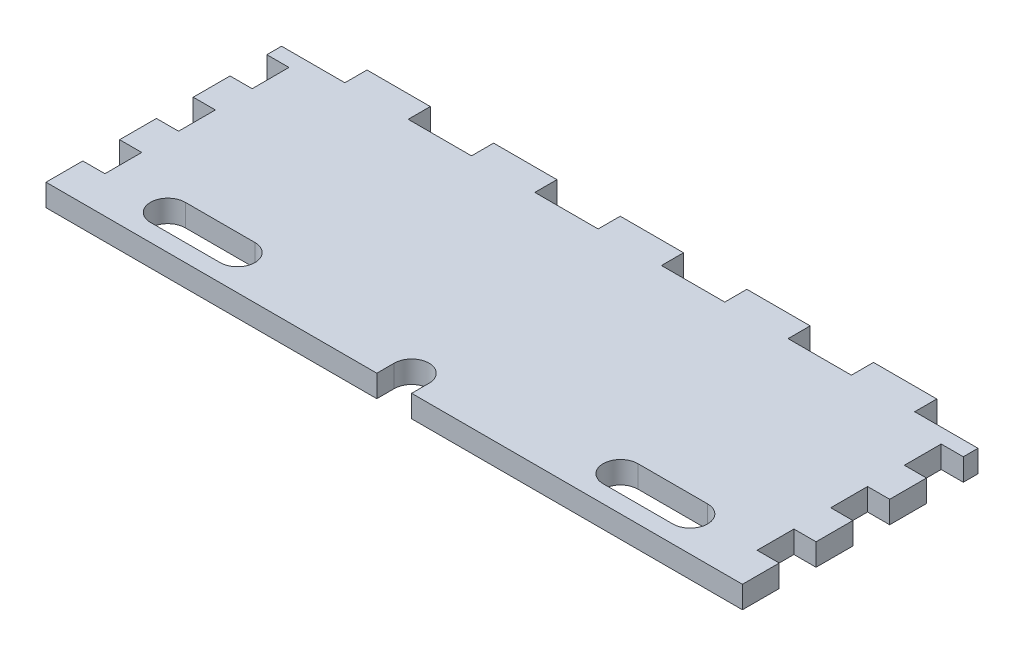
SolidWorks part; units mm, degrees
material "Pin"
ref_plane "Plan de face" through (0, 0, 0) normal (0, 0, 1) x (1, 0, 0)
ref_plane "Plan de dessus" through (0, 0, 0) normal (0, 1, 0) x (1, 0, 0)
ref_plane "Plan de droite" through (0, 0, 0) normal (1, 0, 0) x (0, 0, -1)
sketch "Esquisse1" plane through (0, 0, 0) normal (0, 1, 0) x (1, 0, 0)
  line L1 (-100, 0) -> (100, 0)
  line L2 (-100, 0) -> (-100, 74)
  line L3 (-100, 74) -> (100, 74)
  line L4 (100, 0) -> (100, 74)
  point P4 (0, 0)
  dimension "D1" = 200
  dimension "D2" = 74
extrude "Boss.-Extru.1" add sketch "Esquisse1" along normal blind 6.35
sketch "Esquisse3" plane through (0, 6.35, 0) normal (0, 1, 0) x (1, 0, 0)
  line L0 (-100, 74) -> (-100, 0) construction
  line L1 (-100, 10.5714) -> (-93.65, 10.5714)
  line L2 (-100, 10.5714) -> (-100, 21.1429)
  line L3 (-100, 21.1429) -> (-93.65, 21.1429)
  line L4 (-93.65, 10.5714) -> (-93.65, 21.1429)
  line L5 (-100, 31.7143) -> (-93.65, 31.7143)
  line L6 (-100, 31.7143) -> (-100, 42.2857)
  line L7 (-100, 42.2857) -> (-93.65, 42.2857)
  line L8 (-93.65, 31.7143) -> (-93.65, 42.2857)
  line L10 (-100, 52.8571) -> (-93.65, 52.8571)
  line L11 (-100, 52.8571) -> (-100, 63.4286)
  line L12 (-100, 63.4286) -> (-93.65, 63.4286)
  line L13 (-93.65, 52.8571) -> (-93.65, 63.4286)
  line L18 (-93.65, 63.4286) -> (-93.65, 74) construction
  line L19 (-93.65, 52.8571) -> (-93.65, 42.2857) construction
  line L20 (-93.65, 31.7143) -> (-93.65, 21.1429) construction
  line L21 (100, 74) -> (-100, 74) construction
  line L22 (-93.65, 10.5714) -> (-93.65, 0) construction
  line L23 (-100, 0) -> (100, 0) construction
  dimension "D1" = 6.35
extrude "Enlèv. mat.-Extru.1" cut sketch "Esquisse3" against normal blind 6.35
mirror "Symétrie1" about plane through (0, 0, 0) normal (1, 0, 0) of "Enlèv. mat.-Extru.1"
sketch "Esquisse4" plane through (0, 6.35, 0) normal (0, 1, 0) x (1, 0, 0)
  line L0 (100, 74) -> (-100, 74) construction
  line L1 (-100, 74) -> (-81.8182, 74)
  line L2 (-100, 74) -> (-100, 67.65)
  line L3 (-100, 67.65) -> (-81.8182, 67.65)
  line L4 (-81.8182, 74) -> (-81.8182, 67.65)
  line L5 (-63.6364, 74) -> (-45.4545, 74)
  line L6 (-63.6364, 74) -> (-63.6364, 67.65)
  line L7 (-63.6364, 67.65) -> (-45.4545, 67.65)
  line L8 (-45.4545, 74) -> (-45.4545, 67.65)
  line L9 (-81.8182, 74) -> (-63.6364, 74) construction
  line L10 (-27.2727, 74) -> (-9.0909, 74)
  line L11 (-27.2727, 74) -> (-27.2727, 67.65)
  line L12 (-27.2727, 67.65) -> (-9.0909, 67.65)
  line L13 (-9.0909, 74) -> (-9.0909, 67.65)
  line L14 (9.0909, 74) -> (27.2727, 74)
  line L15 (9.0909, 74) -> (9.0909, 67.65)
  line L16 (9.0909, 67.65) -> (27.2727, 67.65)
  line L17 (27.2727, 74) -> (27.2727, 67.65)
  line L18 (45.4545, 74) -> (63.6364, 74)
  line L19 (45.4545, 74) -> (45.4545, 67.65)
  line L20 (45.4545, 67.65) -> (63.6364, 67.65)
  line L21 (63.6364, 74) -> (63.6364, 67.65)
  line L22 (81.8182, 74) -> (100, 74)
  line L23 (81.8182, 74) -> (81.8182, 67.65)
  line L24 (81.8182, 67.65) -> (100, 67.65)
  line L25 (100, 74) -> (100, 67.65)
  line L26 (-45.4545, 74) -> (-27.2727, 74) construction
  line L27 (-9.0909, 74) -> (9.0909, 74) construction
  line L28 (27.2727, 74) -> (45.4545, 74) construction
  line L29 (63.6364, 74) -> (81.8182, 74) construction
  dimension "D1" = 6.35
extrude "Enlèv. mat.-Extru.2" cut sketch "Esquisse4" against normal blind 6.35
sketch "Esquisse5" plane through (0, 6.35, 0) normal (0, 1, 0) x (1, 0, 0)
  line L0 (-75, 10) -> (-55, 10) construction
  line L1 (-75, 15) -> (-55, 15)
  line L2 (-75, 5) -> (-55, 5)
  line L3 (-100, 0) -> (100, 0) construction
  arc A0 (-75, 15) -> (-75, 5) centre (-75, 10) ccw
  arc A1 (-55, 5) -> (-55, 15) centre (-55, 10) ccw
  point P2 (-65, 10)
  dimension "D2" = 5
  dimension "D1" = 20
  dimension "D3" = 65
  dimension "D4" = 10
extrude "Enlèv. mat.-Extru.3" cut sketch "Esquisse5" against normal blind 6.35
mirror "Symétrie2" about plane through (0, 0, 0) normal (1, 0, 0) of "Enlèv. mat.-Extru.3"
sketch "Esquisse6" plane through (0, 0, 0) normal (0, -1, 0) x (1, 0, 0)
  line L0 (-5, 0) -> (-5, -5)
  line L1 (-100, 0) -> (100, 0) construction
  line L3 (5, -5) -> (5, 0)
  line L4 (5, 0) -> (-5, 0)
  arc A0 (-5, -5) -> (5, -5) centre (0, -5) ccw
  point P8 (0, 0)
  dimension "D2" = 10
  dimension "D1" = 10
  dimension "D3" = 5
extrude "Enlèv. mat.-Extru.4" cut sketch "Esquisse6" against normal blind 6.35
